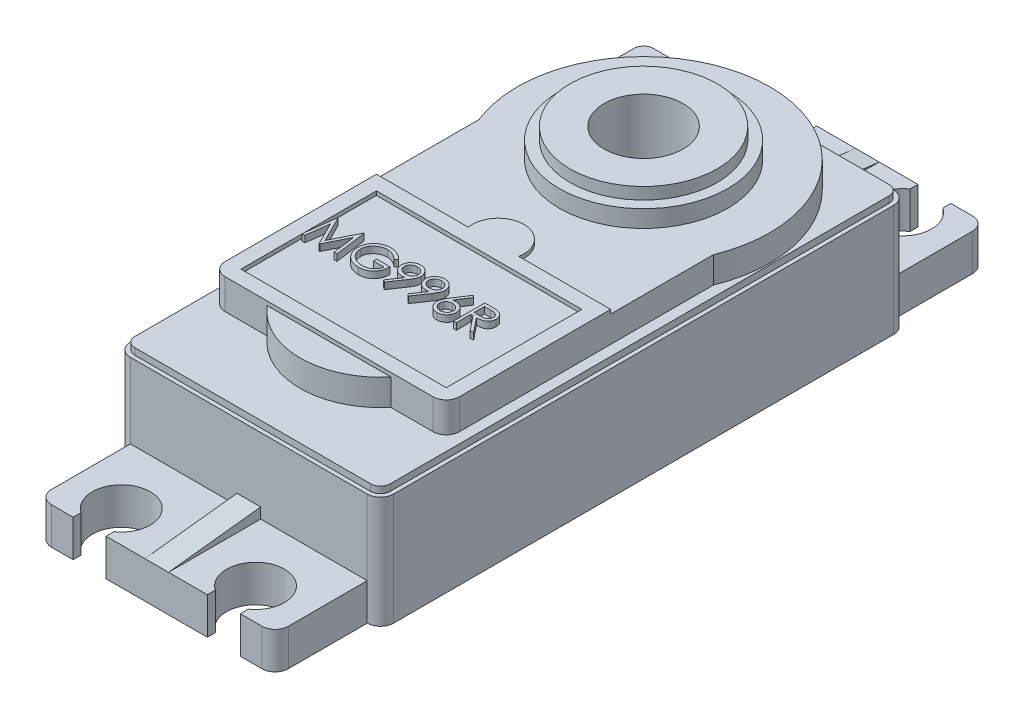
SolidWorks part; units mm, degrees
material "PC High Viscosity"
ref_plane "Front Plane" through (0, 0, 0) normal (0, 0, 1) x (1, 0, 0)
ref_plane "Top Plane" through (0, 0, 0) normal (0, 1, 0) x (1, 0, 0)
ref_plane "Right Plane" through (0, 0, 0) normal (1, 0, 0) x (0, 0, -1)
sketch "BaseS" plane through (0, 0, 0) normal (0, 1, 0) x (1, 0, 0)
  line L1 (-10, 20) -> (10, 20)
  line L2 (-10, 20) -> (-10, -20)
  line L3 (-10, -20) -> (10, -20)
  line L4 (10, 20) -> (10, -20)
  line L5 (-10, 20) -> (10, -20) construction
  line L6 (-10, -20) -> (10, 20) construction
  point P0 (0, 0)
  dimension "D1" = 20
  dimension "D2" = 40
extrude "BASE" add sketch "BaseS" along normal blind 9 contours L4 L3 L2 L1
sketch "ShaftHoleS" plane through (0, 9, 0) normal (0, 1, 0) x (1, 0, 0)
  line L0 (0, 10) -> (0, 20) construction
  line L1 (-10, 20) -> (10, 20) construction
  circle A0 centre (0, 10) radius 3
  dimension "D1" = 6
  dimension "D2" = 10
extrude "SHAFT HOLE" cut sketch "ShaftHoleS" against normal through all
sketch "MountingTabS" plane through (0, 0, 20) normal (0, 0, 1) x (1, 0, 0)
  line L0 (-10, 0) -> (10, 0) construction
  line L1 (-9, 2.8) -> (9, 2.8)
  line L2 (-9, 2.8) -> (-9, 0)
  line L3 (-9, 0) -> (9, 0)
  line L4 (9, 2.8) -> (9, 0)
  line L5 (-9, 2.8) -> (9, 0) construction
  line L6 (-9, 0) -> (9, 2.8) construction
  line L7 (10, 9) -> (10, 0) construction
  point P0 (0, 1.4)
  dimension "D1" = 1
  dimension "D2" = 2.8
  dimension "D3" = 18
extrude "MOUNTING TAB" add sketch "MountingTabS" along normal blind 7
sketch "MountingHoleS" plane through (0, 2.8, 0) normal (0, 1, 0) x (1, 0, 0)
  line L0 (0, -27) -> (0, -20) construction
  line L1 (-6.35, -26.4) -> (-6.35, -27)
  line L2 (-6.35, -27) -> (-3.85, -27)
  line L3 (-3.85, -27) -> (-3.85, -26.4)
  line L4 (-5.1, -24.5896) -> (-5.1, -27) construction
  line L5 (9, -20) -> (-9, -20) construction
  line L6 (9, -27) -> (-9, -27) construction
  line L7 (-9, -27) -> (-9, -20) construction
  arc A0 (-3.85, -26.4) -> (-6.35, -26.4) centre (-5.1, -24.5896) ccw
  dimension "D1" = 4.4
  dimension "D2" = 3.9
  dimension "D3" = 2.5
  dimension "D4" = 0.6
extrude "MOUNTING HOLE" cut sketch "MountingHoleS" against normal through all
mirror "MH M" about plane through (0, 0, 0) normal (1, 0, 0) of "MOUNTING HOLE"
sketch "BottomAlignHoleS" plane through (0, 0, 0) normal (0, -1, 0) x (1, 0, 0)
  line L0 (0, 27) -> (0, 25) construction
  line L1 (-3.85, 27) -> (3.85, 27) construction
  circle A0 centre (0, 25) radius 0.7
  dimension "D1" = 1.4
  dimension "D2" = 2
extrude "BOTTOM ALIGN HOLE" cut sketch "BottomAlignHoleS" against normal blind 0.5
sketch "TriangularTabS" plane through (0, 0, 0) normal (1, 0, 0) x (0, 0, -1)
  line L0 (-20, 2.8) -> (-27, 2.8)
  line L1 (-27, 2.8) -> (-20, 3.6)
  line L2 (-20, 3.6) -> (-20, 2.8)
  line L3 (-26.4, 2.8) -> (-27, 2.8) construction
  dimension "D1" = 0.8
extrude "TRIANGULAR TAB" add sketch "TriangularTabS" along normal mid plane 1.8
mirror "MOUNTING TAB FEATURES M" about plane through (0, 0, 0) normal (0, 0, 1) of "TRIANGULAR TAB", "BOTTOM ALIGN HOLE", "MH M", "MOUNTING HOLE", "MOUNTING TAB"
sketch "BaseTopBodyS" plane through (0, 9, 0) normal (0, 1, 0) x (1, 0, 0)
  line L0 (-8.9, -13.8986) -> (8.9, -13.8986)
  line L1 (8.9, -13.8986) -> (8.9, 6.4014)
  line L2 (-8.9, -13.8986) -> (-8.9, 6.4014)
  line L3 (0, -13.8986) -> (0, 0) construction
  arc A0 (8.9, 6.4014) -> (-8.9, 6.4014) centre (0, 10) ccw
  circle A1 centre (0, 10) radius 3
  circle A2 centre (0, 10) radius 3 construction
  dimension "D1" = 19.2
  dimension "D2" = 17.8
  dimension "D3" = 20.3
extrude "BASE TOP BODY" add sketch "BaseTopBodyS" along normal blind 2
sketch "PartCircleS" plane through (0, 9, 0) normal (0, 1, 0) x (1, 0, 0)
  line L0 (-4.7, -13.8986) -> (4.7, -13.8986) construction
  line L1 (0, -13.8986) -> (0, -16.0986) construction
  line L2 (-4.7, -13.8986) -> (4.7, -13.8986)
  line L3 (-8.9, -13.8986) -> (8.9, -13.8986) construction
  arc A0 (-4.7, -13.8986) -> (4.7, -13.8986) centre (0, -9.9782) ccw
  dimension "D1" = 2.2
  dimension "D2" = 9.4
extrude "PART CIRCLE" add sketch "PartCircleS" along normal up to surface (2 mm away) up to face at (0, 11, 0.449)
sketch "TopBodyCylinder1" plane through (0, 11, 0) normal (0, 1, 0) x (1, 0, 0)
  circle A0 centre (0, 10) radius 3
  circle A1 centre (0, 10) radius 6.4
  circle A2 centre (0, 10) radius 3 construction
  dimension "D1" = 12.8
extrude "TOP BODY CYLINDER 1" add sketch "TopBodyCylinder1" along normal blind 1.3
sketch "TopBodyCylinder2" plane through (0, 12.3, 0) normal (0, 1, 0) x (1, 0, 0)
  circle A0 centre (0, 10) radius 5.6
  circle A1 centre (0, 10) radius 6.4 construction
  circle A2 centre (0, 10) radius 3 construction
  circle A3 centre (0, 10) radius 3
  dimension "D1" = 0.8
  dimension "D2" = 11.2
extrude "TOB BODY CYLINDER 2" add sketch "TopBodyCylinder2" along normal blind 0.9
sketch "TopBodyLabelNest" plane through (0, 11, 0) normal (0, 1, 0) x (1, 0, 0)
  line L0 (-8.9, -1.3986) -> (8.9, -1.3986)
  line L1 (-8.9, -1.3986) -> (-8.9, -13.8986)
  line L2 (-8.9, -13.8986) -> (8.9, -13.8986)
  line L3 (8.9, -1.3986) -> (8.9, -13.8986)
  line L4 (-8.9, -1.3986) -> (8.9, -13.8986) construction
  line L5 (-8.9, -13.8986) -> (8.9, -1.3986) construction
  line L6 (-7.8, -2.4986) -> (7.8, -2.4986)
  line L7 (-7.8, -2.4986) -> (-7.8, -12.7986)
  line L8 (-7.8, -12.7986) -> (7.8, -12.7986)
  line L9 (7.8, -2.4986) -> (7.8, -12.7986)
  line L10 (-7.8, -2.4986) -> (7.8, -12.7986) construction
  line L11 (-7.8, -12.7986) -> (7.8, -2.4986) construction
  line L12 (8.9, -13.8986) -> (8.9, 6.4014) construction
  line L13 (0, -2.4986) -> (0, -1.3986) construction
  line L14 (-7.8, -7.6486) -> (-8.9, -7.6486) construction
  point P0 (0, -7.6486)
  point P5 (0, -7.6486)
  dimension "D1" = 12.5
  dimension "D2" = 1.1
extrude "TOP BODY LABEL NEST" add sketch "TopBodyLabelNest" along normal blind 0.3
sketch "PartCircle2S" plane through (0, 11, 0) normal (0, 1, 0) x (1, 0, 0)
  line L0 (1.3038, -2.4986) -> (-1.3038, -2.4986)
  line L1 (0, -2.4986) -> (0, 3.6) construction
  line L2 (0, 0.9014) -> (0, 3.6) construction
  line L3 (7.8, -2.4986) -> (-7.8, -2.4986) construction
  arc A0 (1.3038, -2.4986) -> (-1.3038, -2.4986) centre (0, -1.0486) ccw
  circle A1 centre (0, 10) radius 6.4 construction
  dimension "D2" = 1.95
  dimension "D1" = 3.4
extrude "PART CIRCLE 2" add sketch "PartCircle2S" along normal up to surface (0.3 mm away) up to face at (0, 11.3, 7.6486)
sketch "BorderCutS" plane through (0, 9, 0) normal (0, 1, 0) x (1, 0, 0)
  line L0 (-9.7, 19.7) -> (-9.7, -19.7)
  line L1 (-9.7, -19.7) -> (9.7, -19.7)
  line L2 (9.7, -19.7) -> (9.7, 19.7)
  line L3 (9.7, 19.7) -> (-9.7, 19.7)
  line L4 (-10, 20) -> (-10, -20)
  line L5 (-10, -20) -> (10, -20)
  line L6 (10, -20) -> (10, 20)
  line L7 (10, 20) -> (-10, 20)
  line L8 (-10, 0) -> (-9.7, 0) construction
  line L9 (0, -20) -> (0, -19.7) construction
  dimension "D1" = 0.3
extrude "BORDER CUT" cut sketch "BorderCutS" against normal blind 0.5
fillet "MAIN BODY FEATURES F" radius 1 10 edges at (9, 1.4, -27) (-9, 1.4, -27) (-10, 4.25, -20) (10, 4.25, -20) (-8.9, 10.15, 13.8986) (8.9, 10.15, 13.8986) (-10, 4.25, 20) (10, 4.25, 20) (9, 1.4, 27) (-9, 1.4, 27)
fillet "BORDER CUT F" radius 0.75 4 edges at (-9.7, 8.75, -19.7) (9.7, 8.75, -19.7) (9.7, 8.75, 19.7) (-9.7, 8.75, 19.7)
sketch "Esquisse1" plane through (0, 11, 0) normal (0, 1, 0) x (1, 0, 0)
  line L0 (-7.8, -2.4986) -> (-7.8, -12.7986) construction
  text T0 "MG996R\r\n\r\n" font "Century Gothic" height in points 9
extrude "Boss.-Extru.1" add sketch "Esquisse1" along normal blind 0.5
